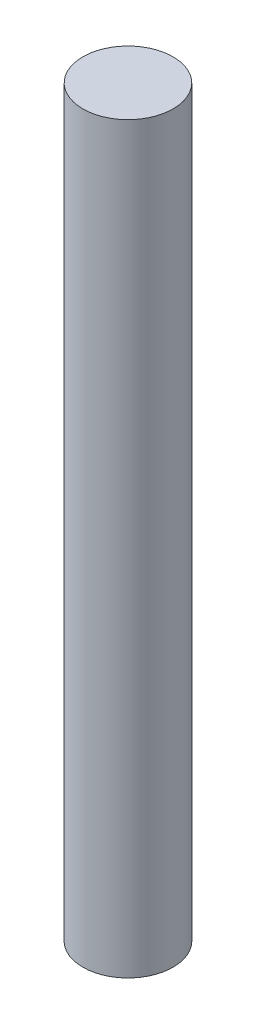
SolidWorks part; units mm, degrees
ref_plane "Front Plane" through (0, 0, 0) normal (0, 0, 1) x (1, 0, 0)
ref_plane "Top Plane" through (0, 0, 0) normal (0, 1, 0) x (1, 0, 0)
ref_plane "Right Plane" through (0, 0, 0) normal (1, 0, 0) x (0, 0, -1)
sketch "Sketch2" plane through (0, 0, 0) normal (0, 1, 0) x (1, 0, 0)
  circle A0 centre (0, 0) radius 0.85
  dimension "D1" = 1.7
extrude "Boss-Extrude1" add sketch "Sketch2" along normal blind 14
